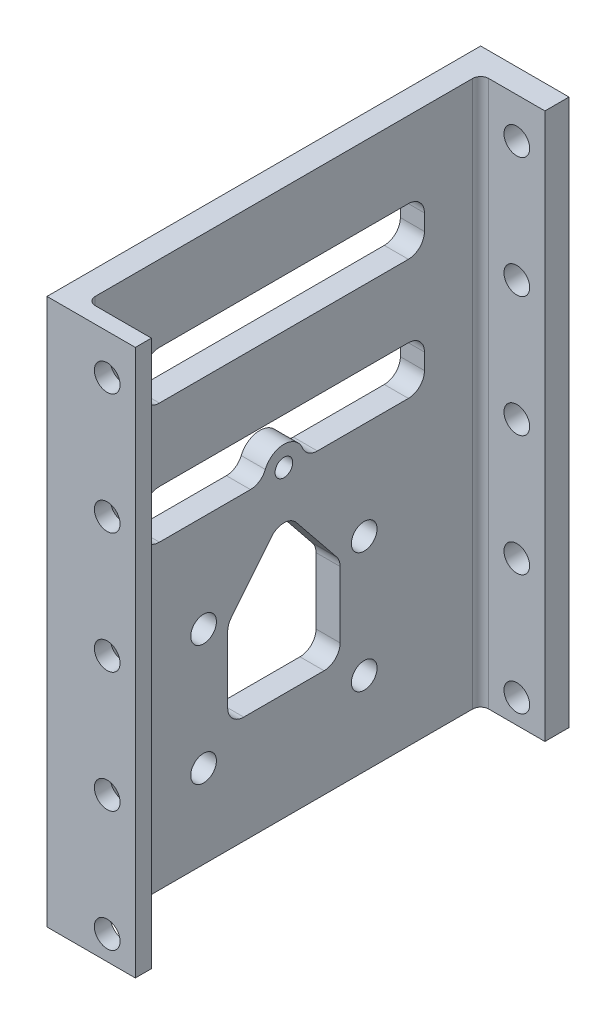
SolidWorks part; units mm, degrees
material "PET"
ref_plane "前视基准面" through (0, 0, 0) normal (0, 0, 1) x (1, 0, 0)
ref_plane "上视基准面" through (0, 0, 0) normal (0, 1, 0) x (1, 0, 0)
ref_plane "右视基准面" through (0, 0, 0) normal (1, 0, 0) x (0, 0, -1)
other "Configuration Table"
sketch "草图1" plane through (0, 0, 0) normal (0, 1, 0) x (1, 0, 0)
  line L0 (0, 0) -> (8, 0)
  line L1 (8, 0) -> (8, -3)
  line L2 (8, -3) -> (-3, -3)
  line L3 (-3, -3) -> (-3, 49)
  line L4 (-3, 49) -> (0, 49)
  line L5 (0, 49) -> (0, 0)
  dimension "D1" = 3
  dimension "D2" = 3
  dimension "D3" = 52
  dimension "D4" = 8
extrude "凸台-拉伸1" add sketch "草图1" along normal blind 120
sketch "草图2" plane through (0, 0, 0) normal (0, 0, -1) x (-1, 0, 0)
  line L0 (-8, 60) -> (-4.5, 60) construction
  line L1 (-8, 120) -> (-8, 0) construction
  line L2 (-4.5, 60) -> (-4.5, 45) construction
  line L3 (-8, 60) -> (3, 60) construction
  line L4 (3, 120) -> (3, 0) construction
  line L5 (0, 120) -> (0, 0) construction
  circle A0 centre (-4.5, 60) radius 1.6
  circle A1 centre (-4.5, 45) radius 1.6
  circle A2 centre (-4.5, 30) radius 1.6
  circle A3 centre (-4.5, 15) radius 1.6
  circle A4 centre (-4.5, 75) radius 1.6
  circle A5 centre (-4.5, 90) radius 1.6
  circle A6 centre (-4.5, 105) radius 1.6
  dimension "D2" = 3.2
  dimension "D1" = 4.5
  dimension "D4" = 15
  dimension "D3" = 4
extrude "切除-拉伸1" cut sketch "草图2" against normal blind 120
sketch "草图3" plane through (0, 0, 0) normal (1, 0, 0) x (0, 0, -1)
  line L0 (0, 120) -> (49, 120) construction
  line L1 (24.5, 120) -> (24.5, 0) construction
  line L2 (0, 0) -> (49, 0) construction
  line L3 (24.5, 7.3845) -> (14.5, 7.3845) construction
  circle A0 centre (14.5, 7.3845) radius 1.6
  circle A1 centre (14.5, 22.3845) radius 1.6
  circle A2 centre (14.5, 37.3845) radius 1.6
  circle A3 centre (14.5, 52.3845) radius 1.6
  circle A4 centre (14.5, 67.3845) radius 1.6
  circle A5 centre (34.5, 67.3845) radius 1.6
  circle A6 centre (34.5, 52.3845) radius 1.6
  circle A7 centre (34.5, 37.3845) radius 1.6
  circle A8 centre (34.5, 22.3845) radius 1.6
  circle A9 centre (34.5, 7.3845) radius 1.6
  dimension "D2" = 3.2
  dimension "D1" = 10
  dimension "D3" = 5
extrude "切除-拉伸2" cut sketch "草图3" against normal blind 10
sketch "草图4" plane through (0, 0, 0) normal (1, 0, 0) x (0, 0, -1)
  line L0 (0, 120) -> (49, 120) construction
  line L1 (24.5, 120) -> (24.5, 0) construction
  line L2 (0, 0) -> (49, 0) construction
  line L3 (24.5, 117) -> (15.7, 117) construction
  circle A0 centre (15.7, 117) radius 1.1
  circle A1 centre (33.3, 117) radius 1.1
  circle A2 centre (24.5, 79.8) radius 1.1
  dimension "D2" = 2.2
  dimension "D3" = 37.2
  dimension "D4" = 2.2
  dimension "D1" = 8.8
  dimension "D5" = 3
extrude "切除-拉伸3" cut sketch "草图4" against normal blind 12
ref_plane "基准面1" through (0, 0, -24.5) normal (0, 0, -1) x (-1, 0, 0)
sketch "草图5" plane through (0, 0, -49) normal (0, 0, -1) x (-1, 0, 0)
  line L1 (3, 120) -> (-8, 120)
  line L2 (3, 120) -> (3, 0)
  line L3 (3, 0) -> (-8, 0)
  line L4 (-8, 120) -> (-8, 0)
extrude "凸台-拉伸2" add sketch "草图5" along normal blind 2
mirror "镜向3" about plane through (0, 0, -24.5) normal (0, 0, -1) of "切除-拉伸1"
sketch "草图6" plane through (0, 0, 0) normal (1, 0, 0) x (0, 0, -1)
  line L0 (0, 0) -> (0, 30)
  line L1 (0, 120) -> (0, 0) construction
  line L2 (0, 30) -> (49, 30)
  line L3 (49, 120) -> (49, 0) construction
  line L4 (49, 30) -> (49, 0)
  line L5 (49, 0) -> (0, 0)
  dimension "D1" = 30
extrude "切除-拉伸4" cut sketch "草图6" against normal blind 10
sketch "草图7" plane through (0, 0, 0) normal (1, 0, 0) x (0, 0, -1)
  line L0 (0, 30) -> (-3, 30)
  line L1 (-3, 120) -> (-3, 0) construction
  line L2 (-3, 30) -> (-3, 0)
  line L3 (-3, 0) -> (0, 0)
  line L4 (0, 0) -> (0, 30)
extrude "切除-拉伸5" cut sketch "草图7" against normal blind 16 and the other way blind 42
sketch "草图8" plane through (0, 0, 0) normal (1, 0, 0) x (0, 0, -1)
  line L0 (49, 120) -> (49, 30) construction
  line L1 (-3, 30) -> (49, 30)
  line L2 (-3, 30) -> (-3, 42)
  line L3 (-3, 42) -> (49, 42)
  line L4 (49, 30) -> (49, 42)
  dimension "D1" = 12
extrude "切除-拉伸6" cut sketch "草图8" against normal blind 11 and the other way blind 35
sketch "草图9" plane through (-3, 0, 0) normal (-1, 0, 0) x (0, 0, 1)
  line L1 (-51, 0) -> (-49, 0)
  line L2 (-51, 0) -> (-51, 42)
  line L3 (-51, 42) -> (-49, 42)
  line L4 (-49, 0) -> (-49, 42)
extrude "切除-拉伸7" cut sketch "草图9" against normal blind 20
sketch "草图10" plane through (0, 120, 0) normal (0, 1, 0) x (1, 0, 0)
  line L1 (-3, 51) -> (8, 51)
  line L2 (-3, 51) -> (-3, -3)
  line L3 (-3, -3) -> (8, -3)
  line L4 (8, 51) -> (8, -3)
extrude "切除-拉伸8" cut sketch "草图10" against normal blind 10
sketch "草图11" plane through (0, 0, -51) normal (0, 0, -1) x (-1, 0, 0)
  line L4 (3, 110) -> (-8, 110)
  line L5 (-8, 110) -> (-8, 42)
  line L6 (-8, 42) -> (3, 42)
  line L7 (3, 42) -> (3, 110)
  line L8 (3, 110) -> (-8, 110)
  line L9 (-8, 110) -> (-8, 42)
  line L10 (-8, 42) -> (3, 42)
  line L11 (3, 42) -> (3, 110)
  circle A0 centre (-4.5, 105) radius 1.6 construction
  circle A1 centre (-4.5, 105) radius 1.6
  circle A2 centre (-4.5, 45) radius 1.6 construction
  circle A3 centre (-4.5, 60) radius 1.6 construction
  circle A4 centre (-4.5, 75) radius 1.6 construction
  circle A5 centre (-4.5, 90) radius 1.6 construction
  circle A6 centre (-4.5, 45) radius 1.6
  circle A7 centre (-4.5, 60) radius 1.6
  circle A8 centre (-4.5, 75) radius 1.6
  circle A9 centre (-4.5, 90) radius 1.6
  dimension "D1" = 0
extrude "凸台-拉伸3" add sketch "草图11" along normal blind 1
sketch "草图12" plane through (0, 110, 0) normal (0, 1, 0) x (1, 0, 0)
  line L0 (8, -3) -> (8, 0) construction
  line L1 (-3, -3) -> (8, -3)
  line L2 (-3, -3) -> (-3, -2)
  line L3 (-3, -2) -> (8, -2)
  line L4 (8, -3) -> (8, -2)
  dimension "D1" = 1
extrude "切除-拉伸9" cut sketch "草图12" against normal blind 91
sketch "草图13" plane through (-3, 0, 0) normal (-1, 0, 0) x (0, 0, 1)
  line L0 (-34.5, 67.3845) -> (-24.5, 79.8) construction
  line L1 (-24.5, 79.8) -> (-14.5, 67.3845) construction
  line L2 (-14.5, 67.3845) -> (-14.5, 52.3845) construction
  line L3 (-14.5, 52.3845) -> (-34.5, 52.3845) construction
  line L4 (-34.5, 52.3845) -> (-34.5, 67.3845) construction
  line L5 (-31.5, 66.3265) -> (-24.5, 75.0174)
  line L6 (-24.5, 75.0174) -> (-17.5, 66.3265)
  line L7 (-17.5, 66.3265) -> (-17.5, 55.3845)
  line L8 (-17.5, 55.3845) -> (-31.5, 55.3845)
  line L9 (-31.5, 55.3845) -> (-31.5, 66.3265)
  dimension "D1" = 3
extrude "切除-拉伸10" cut sketch "草图13" against normal blind 10
sketch "草图14" plane through (-3, 0, 0) normal (-1, 0, 0) x (0, 0, 1)
  line L0 (-49, 103.4) -> (-49, 91.6) construction
  line L1 (-49, 97.5) -> (0, 97.5) construction
  line L2 (0, 110) -> (0, 42) construction
  line L3 (-49, 88.4) -> (-49, 76.6) construction
  line L4 (-42, 94.5) -> (-7, 94.5)
  line L5 (-42, 94.5) -> (-42, 100.5)
  line L6 (-42, 100.5) -> (-7, 100.5)
  line L7 (-7, 94.5) -> (-7, 100.5)
  line L8 (-42, 94.5) -> (-7, 100.5) construction
  line L9 (-42, 100.5) -> (-7, 94.5) construction
  line L10 (-49, 82.5) -> (0, 82.5) construction
  line L11 (-22.0181, 79.5) -> (-7, 79.5)
  line L12 (-42, 79.5) -> (-26.9819, 79.5)
  line L13 (-42, 79.5) -> (-42, 85.5)
  line L14 (-42, 85.5) -> (-7, 85.5)
  line L15 (-7, 79.5) -> (-7, 85.5)
  line L16 (-42, 79.5) -> (-7, 85.5) construction
  line L17 (-42, 85.5) -> (-7, 79.5) construction
  arc A0 (-22.0181, 79.5) -> (-26.9819, 79.5) centre (-24.5, 79.8) ccw
  point P8 (-24.5, 97.5)
  point P19 (-24.5, 82.5)
  dimension "D4" = 5
  dimension "D1" = 35
  dimension "D2" = 6
  dimension "D3" = 6
extrude "切除-拉伸11" cut sketch "草图14" against normal blind 10
fillet "圆角1" radius 2 15 edges at (-1.5, 94.5, -7) (-1.5, 100.5, -7) (-1.5, 100.5, -42) (-1.5, 94.5, -42) (-1.5, 79.5, -42) (-1.5, 85.5, -42) (-1.5, 85.5, -7) (-1.5, 79.5, -7) (-1.5, 79.5, -22.0181) (-1.5, 79.5, -26.9819) (-1.5, 66.3265, -17.5) (-1.5, 55.3845, -17.5) (-1.5, 55.3845, -31.5) (-1.5, 66.3265, -31.5) (-1.5, 75.0174, -24.5)
fillet "圆角2" radius 1 2 edges at (0, 76, 0) (0, 76, -49)
